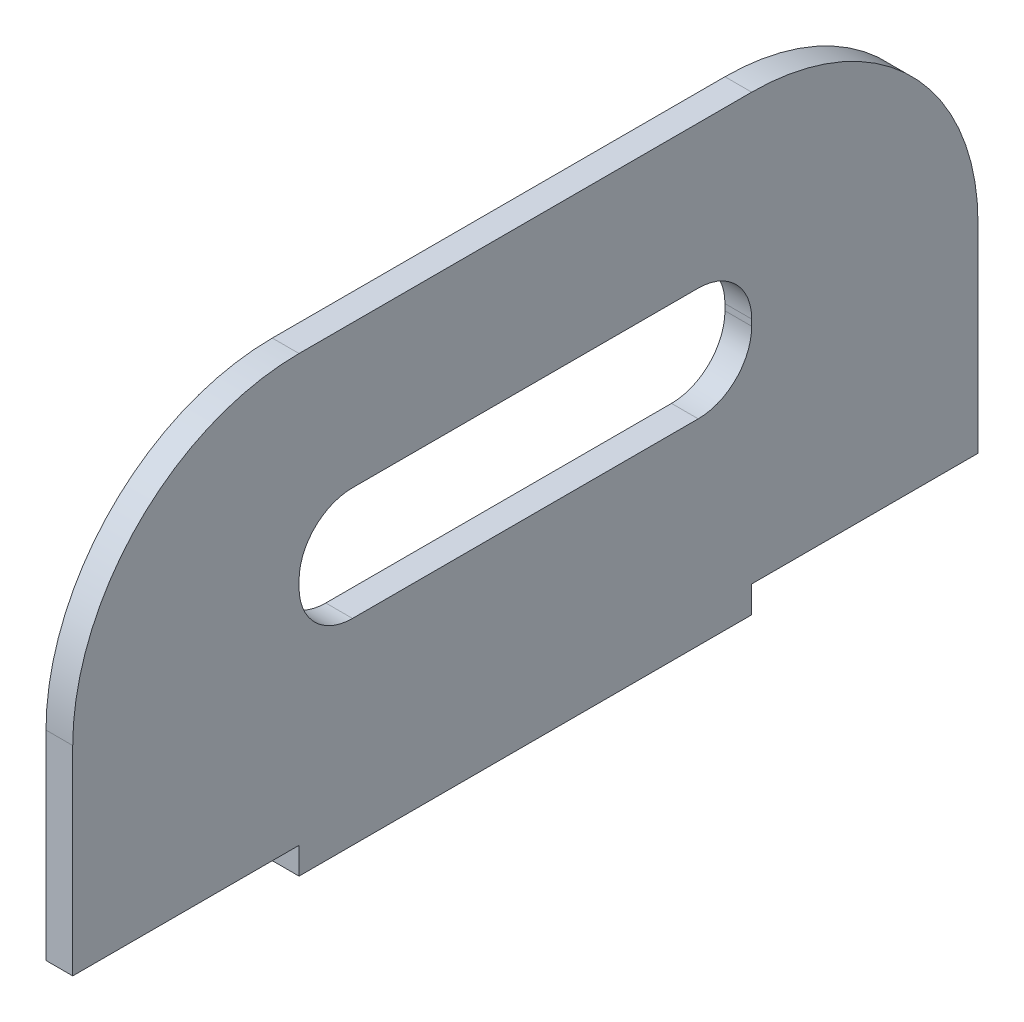
SolidWorks part; units mm, degrees
ref_plane "Front Plane" through (0, 0, 0) normal (0, 0, 1) x (1, 0, 0)
ref_plane "Top Plane" through (0, 0, 0) normal (0, 1, 0) x (1, 0, 0)
ref_plane "Right Plane" through (0, 0, 0) normal (1, 0, 0) x (0, 0, -1)
sketch "Sketch2" plane through (0, 0, 0) normal (1, 0, 0) x (0, 0, -1)
  line L1 (0, 0) -> (101.6, 0)
  line L2 (0, 0) -> (0, 50.8)
  line L3 (0, 50.8) -> (101.6, 50.8)
  line L4 (101.6, 0) -> (101.6, 50.8)
  dimension "D1" = 50.8
  dimension "D2" = 101.6
extrude "Boss-Extrude1" add sketch "Sketch2" along normal blind 3
fillet "Fillet1" radius 25.4 2 edges at (1.5, 50.8, -101.6) (1.5, 50.8, 0)
sketch "Sketch4" plane through (3, 0, 0) normal (1, 0, 0) x (0, 0, -1)
  line L1 (0, 0) -> (25.4, 0)
  line L2 (0, 0) -> (0, 3)
  line L3 (0, 3) -> (25.4, 3)
  line L4 (25.4, 0) -> (25.4, 3)
  line L5 (101.6, 0) -> (76.2, 0)
  line L6 (101.6, 0) -> (101.6, 3)
  line L7 (101.6, 3) -> (76.2, 3)
  line L8 (76.2, 0) -> (76.2, 3)
  dimension "D1" = 3
  dimension "D2" = 3
  dimension "D3" = 25.4
extrude "Cut-Extrude1" cut sketch "Sketch4" against normal blind 3
sketch "Sketch6" plane through (3, 0, 0) normal (1, 0, 0) x (0, 0, -1)
  line L0 (0, 25.4) -> (0, 3) construction
  line L1 (25.4, 22.05) -> (76.2, 22.05)
  line L2 (25.4, 22.05) -> (25.4, 34.75)
  line L3 (25.4, 34.75) -> (76.2, 34.75)
  line L4 (76.2, 22.05) -> (76.2, 34.75)
  line L6 (101.6, 3) -> (76.2, 3) construction
  point P6 (50.8, 34.75)
  point P7 (76.2, 28.4)
  dimension "D1" = 50.8
  dimension "D2" = 12.7
  dimension "D3" = 50.8
  dimension "D4" = 25.4
extrude "Cut-Extrude2" cut sketch "Sketch6" against normal blind 10
fillet "Fillet2" radius 6 4 edges at (1.5, 22.05, -25.4) (1.5, 22.05, -76.2) (1.5, 34.75, -76.2) (1.5, 34.75, -25.4)
